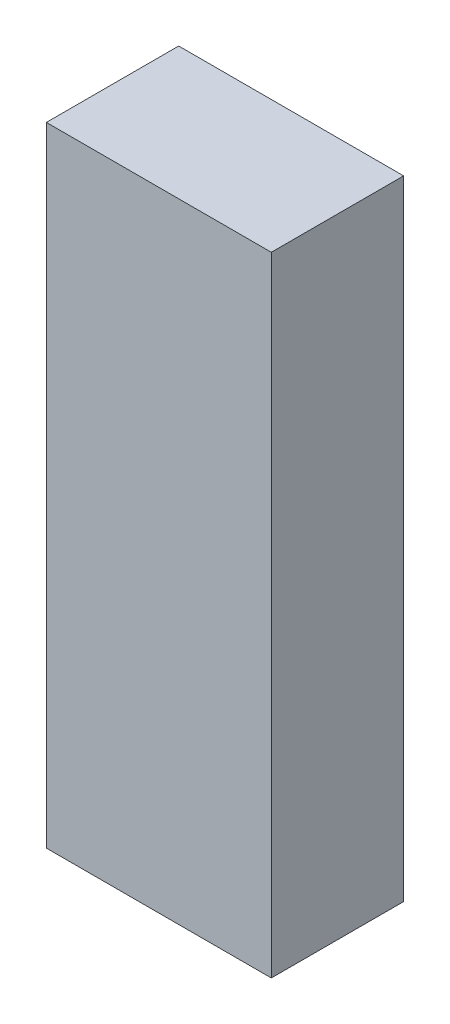
SolidWorks part; units mm, degrees
ref_plane "Front Plane" through (0, 0, 0) normal (1, 0, 0) x (0, 1, 0)
ref_plane "Top Plane" through (0, 0, 0) normal (0, 0, 1) x (0, 1, 0)
ref_plane "Right Plane" through (0, 0, 0) normal (0, 1, 0) x (-1, 0, 0)
sketch "Sketch1" plane through (0, 0, 0) normal (0, 0, 1) x (0, 1, 0)
  line L1 (0, 0) -> (95, 0)
  line L2 (0, 0) -> (0, 34)
  line L3 (0, 34) -> (95, 34)
  line L4 (95, 0) -> (95, 34)
  dimension "D1" = 95
  dimension "D2" = 34
extrude "Boss-Extrude1" add sketch "Sketch1" along normal blind 20
